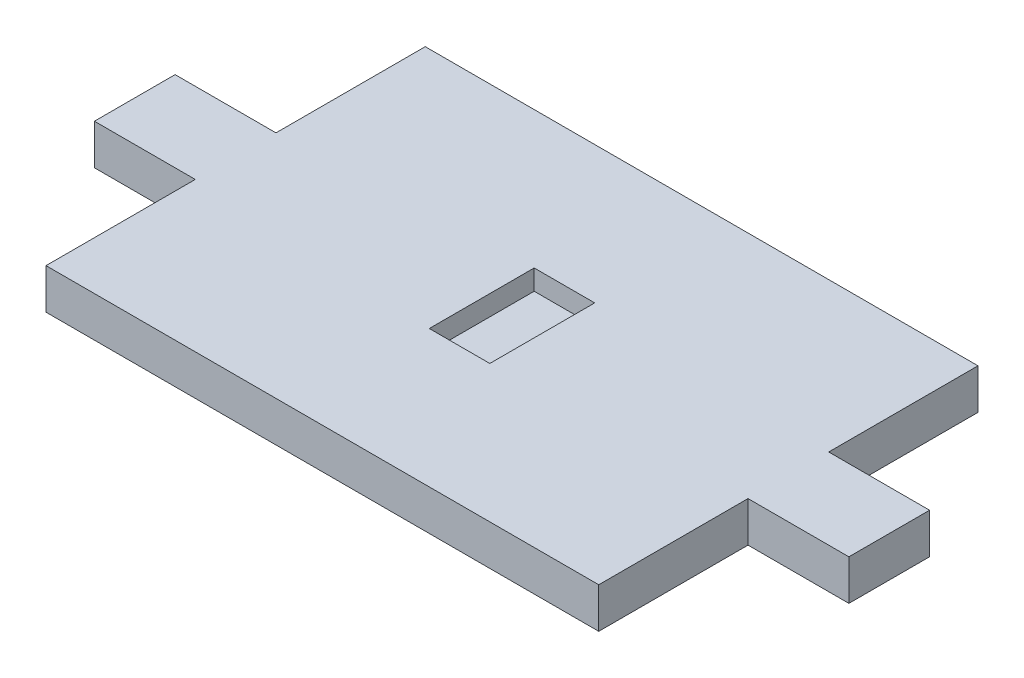
SolidWorks part; units mm, degrees
material "PLA"
ref_plane "Alzado" through (0, 0, 0) normal (0, 0, 1) x (1, 0, 0)
ref_plane "Planta" through (0, 0, 0) normal (0, 1, 0) x (1, 0, 0)
ref_plane "Vista lateral" through (0, 0, 0) normal (1, 0, 0) x (0, 0, -1)
sketch "Croquis1" plane through (0, 0, 0) normal (0, 1, 0) x (1, 0, 0)
  line L0 (-1.198, 0) -> (1.3674, 0) construction
  line L1 (93.5, -10) -> (68.5, -10)
  line L2 (93.5, -10) -> (93.5, 10)
  line L3 (93.5, 10) -> (68.5, 10)
  line L4 (-93.5, -10) -> (-93.5, 10)
  line L5 (93.5, -10) -> (-93.5, 10) construction
  line L6 (93.5, 10) -> (-93.5, -10) construction
  line L8 (-68.5, 10) -> (-68.5, 47)
  line L9 (-68.5, 47) -> (68.5, 47)
  line L10 (68.5, 10) -> (68.5, 47)
  line L11 (-68.5, -47) -> (68.5, -47)
  line L12 (68.5, -10) -> (68.5, -47)
  line L14 (-68.5, -10) -> (-68.5, -47)
  line L15 (-68.5, 10) -> (-93.5, 10)
  line L16 (-68.5, -10) -> (-93.5, -10)
  point P0 (0, 0)
  dimension "D1" = 20
  dimension "D2" = 187
  dimension "D3" = 25
  dimension "D4" = 25
  dimension "D5" = 37
extrude "Saliente-Extruir1" add sketch "Croquis1" along normal blind 10
sketch "Croquis3" plane through (0, 10, 0) normal (0, 1, 0) x (1, 0, 0)
  line L1 (7.5, 13) -> (-7.5, 13)
  line L2 (7.5, 13) -> (7.5, -13)
  line L3 (7.5, -13) -> (-7.5, -13)
  line L4 (-7.5, 13) -> (-7.5, -13)
  line L5 (7.5, 13) -> (-7.5, -13) construction
  line L6 (7.5, -13) -> (-7.5, 13) construction
  point P0 (0, 0)
  dimension "D1" = 15
  dimension "D2" = 26
extrude "Cortar-Extruir3" cut sketch "Croquis3" against normal blind 5
